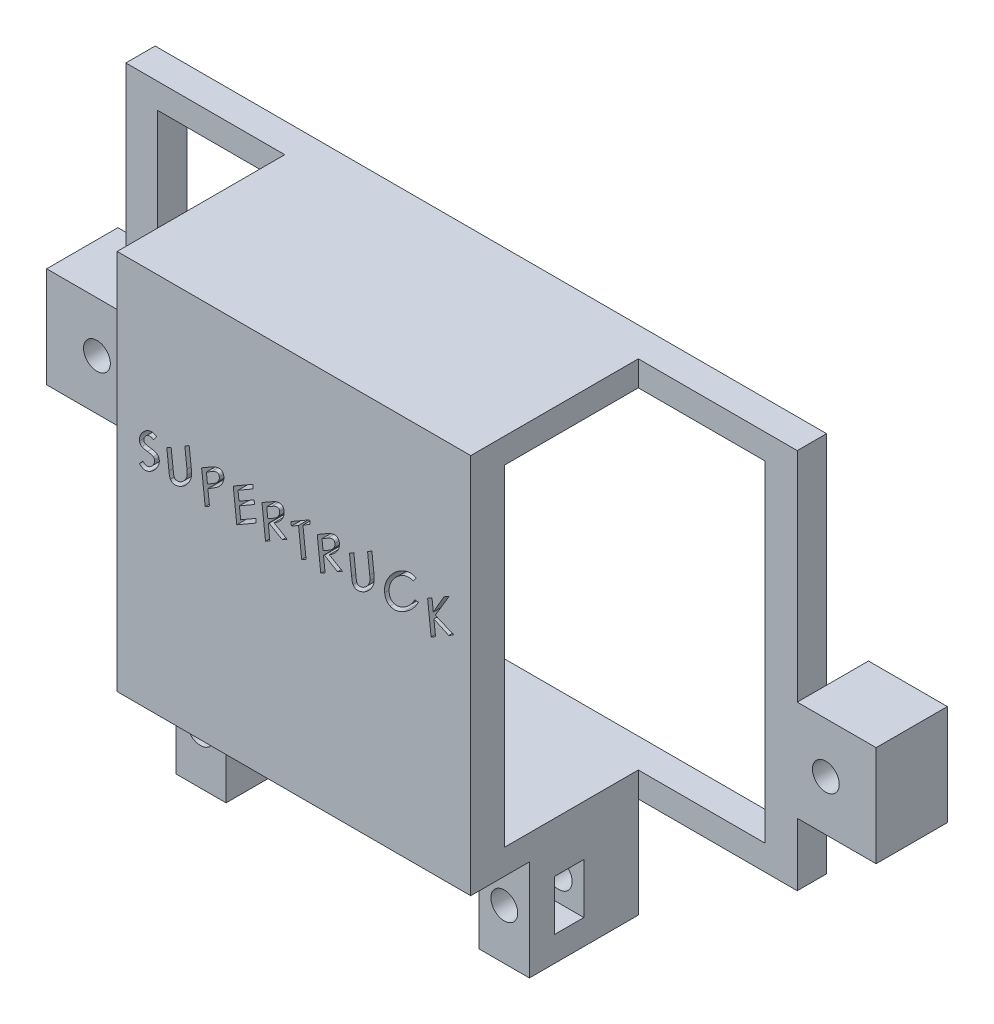
SolidWorks part; units mm, degrees
ref_plane "Plano frontal" through (0, 0, 0) normal (0, 0, 1) x (1, 0, 0)
ref_plane "Plano superior" through (0, 0, 0) normal (0, 1, 0) x (1, 0, 0)
ref_plane "Plano direito" through (0, 0, 0) normal (1, 0, 0) x (0, 0, -1)
sketch "Esboço1" plane through (0, 0, 0) normal (0, 0, 1) x (1, 0, 0)
  line L0 (0, 0) -> (0, 10.5) construction
  line L1 (0, 0) -> (-72.5, 0)
  line L2 (0, 0) -> (0, 39.5)
  line L3 (0, 39.5) -> (-72.5, 39.5)
  line L4 (-72.5, 0) -> (-72.5, 39.5)
  line L5 (-72.5, 0) -> (-72.5, 10.5) construction
  line L6 (0, 10.5) -> (7.25, 10.5) construction
  line L7 (-72.5, 10.5) -> (-79.75, 10.5) construction
  line L8 (-72.5, 39.5) -> (-75.5, 39.5) construction
  line L9 (-72.5, 39.5) -> (-72.5, 42.5) construction
  line L10 (0, 0) -> (3, 0) construction
  line L11 (0, 0) -> (0, -3) construction
  line L12 (-79.75, 10.5) -> (-79.75, 16.5) construction
  line L13 (-76.3022, 42.5) -> (3.836, 42.5)
  line L14 (-76.3022, 42.5) -> (-76.3022, -3)
  line L15 (-76.3022, -3) -> (3.836, -3)
  line L16 (3.836, 42.5) -> (3.836, -3)
  line L17 (-79.75, 10.5) -> (-85.75, 10.5) construction
  line L18 (-79.75, 10.5) -> (-79.75, 4.5) construction
  line L19 (7.25, 10.5) -> (7.25, 16.5) construction
  line L20 (7.25, 10.5) -> (13.25, 10.5) construction
  line L21 (7.25, 10.5) -> (7.25, 4.5) construction
  line L23 (-85.75, 16.5) -> (-76.3022, 16.5)
  line L24 (-85.75, 16.5) -> (-85.75, 4.5)
  line L25 (-85.75, 4.5) -> (-76.3022, 4.5)
  line L26 (-76.3022, 16.5) -> (-76.3022, 4.5)
  line L27 (13.25, 4.5) -> (3.836, 4.5)
  line L28 (13.25, 4.5) -> (13.25, 16.5)
  line L29 (13.25, 16.5) -> (3.836, 16.5)
  line L30 (3.836, 4.5) -> (3.836, 16.5)
  circle A0 centre (-79.75, 10.5) radius 1.6
  circle A1 centre (7.25, 10.5) radius 1.6
extrude "Ressalto-extrusão1" add sketch "Esboço1" along normal blind 5 contours L24 L25 L14 L23 A0 | L28 L29 L16 L27 A1
ref_plane "Plano1" through (0, 0, 5) normal (0, 0, 1) x (1, 0, 0)
sketch "Esboço2" plane through (0, 0, 5) normal (0, 0, 1) x (1, 0, 0)
  line L4 (-72.5, 0) -> (0, 0)
  line L5 (-72.5, 39.5) -> (-72.5, 0)
  line L6 (0, 39.5) -> (-72.5, 39.5)
  line L7 (0, 0) -> (0, 39.5)
  line L8 (-72.5, 0) -> (0, 0)
  line L9 (-72.5, 39.5) -> (-72.5, 0)
  line L10 (0, 39.5) -> (-72.5, 39.5)
  line L11 (0, 0) -> (0, 39.5)
  line L12 (-76.3022, 16.5) -> (-85.75, 16.5)
  line L13 (-76.3022, 4.5) -> (-76.3022, 16.5)
  line L14 (-85.75, 4.5) -> (-76.3022, 4.5)
  line L15 (-85.75, 16.5) -> (-85.75, 4.5)
  line L16 (-76.3022, 16.5) -> (-85.75, 16.5)
  line L17 (-76.3022, 4.5) -> (-76.3022, 16.5)
  line L18 (-85.75, 4.5) -> (-76.3022, 4.5)
  line L19 (-85.75, 16.5) -> (-85.75, 4.5)
  line L20 (3.836, 42.5) -> (-76.3022, 42.5)
  line L21 (-76.3022, 42.5) -> (-76.3022, -3)
  line L22 (-76.3022, -3) -> (3.836, -3)
  line L23 (3.836, -3) -> (3.836, 42.5)
  line L24 (3.836, 42.5) -> (-76.3022, 42.5)
  line L25 (-76.3022, 42.5) -> (-76.3022, -3)
  line L26 (-76.3022, -3) -> (3.836, -3)
  line L27 (3.836, -3) -> (3.836, 42.5)
  line L28 (3.836, 4.5) -> (13.25, 4.5)
  line L29 (13.25, 4.5) -> (13.25, 16.5)
  line L30 (13.25, 16.5) -> (3.836, 16.5)
  line L31 (3.836, 16.5) -> (3.836, 4.5)
  line L32 (3.836, 4.5) -> (13.25, 4.5)
  line L33 (13.25, 4.5) -> (13.25, 16.5)
  line L34 (13.25, 16.5) -> (3.836, 16.5)
  line L35 (3.836, 16.5) -> (3.836, 4.5)
  circle A1 centre (7.25, 10.5) radius 1.6
  circle A2 centre (7.25, 10.5) radius 1.6
  circle A3 centre (-79.75, 10.5) radius 1.6
  circle A4 centre (-79.75, 10.5) radius 1.6
  dimension "D1" = 0
  dimension "D2" = 0
  dimension "D3" = 0
  dimension "D4" = 0
  dimension "D5" = 0
  dimension "D6" = 0
extrude "Ressalto-extrusão2" add sketch "Esboço2" along normal blind 3.5 contours L26 L27 L24 L25 L17 L11 L8 L9 L10 | L16 L19 L18 L17 A4 | L33 L34 L27 L32 A2
sketch "Esboço4" plane through (0, 0, 8.5) normal (0, 0, 1) x (1, 0, 0)
  line L0 (-36.25, 0) -> (-36.25, -21.3357) construction
  line L1 (-72.5, 0) -> (0, 0) construction
  line L2 (-36.2331, -3) -> (-21.1331, -3) construction
  line L3 (-36.2331, -3) -> (-51.3331, -3) construction
  line L4 (-51.3331, -3) -> (-51.3331, -15)
  line L5 (-21.1331, -15) -> (-21.1331, -3)
  line L6 (-21.1331, -15) -> (-15.1331, -15)
  line L7 (-15.1331, -15) -> (-15.1331, 0)
  line L8 (-15.1331, 0) -> (-51.3331, 0)
  line L9 (-51.3331, -15) -> (-57.3331, -15)
  line L10 (-57.3331, -15) -> (-57.3331, 0)
  line L11 (-57.3331, 0) -> (-51.3331, 0)
  line L12 (-76.3022, -3) -> (3.836, -3)
  line L13 (3.836, -3) -> (3.836, 4.5)
  line L14 (3.836, 4.5) -> (13.25, 4.5)
  line L15 (13.25, 4.5) -> (13.25, 16.5)
  line L16 (13.25, 16.5) -> (3.836, 16.5)
  line L17 (3.836, 16.5) -> (3.836, 42.5)
  line L18 (3.836, 42.5) -> (-76.3022, 42.5)
  line L19 (-76.3022, 42.5) -> (-76.3022, 16.5)
  line L20 (-76.3022, 16.5) -> (-85.75, 16.5)
  line L21 (-85.75, 16.5) -> (-85.75, 4.5)
  line L22 (-85.75, 4.5) -> (-76.3022, 4.5)
  line L23 (-76.3022, 4.5) -> (-76.3022, -3)
  line L24 (-76.3022, -3) -> (3.836, -3)
  line L25 (3.836, -3) -> (3.836, 4.5)
  line L26 (3.836, 4.5) -> (13.25, 4.5)
  line L27 (13.25, 4.5) -> (13.25, 16.5)
  line L28 (13.25, 16.5) -> (3.836, 16.5)
  line L29 (3.836, 16.5) -> (3.836, 42.5)
  line L30 (3.836, 42.5) -> (-76.3022, 42.5)
  line L31 (-76.3022, 42.5) -> (-76.3022, 16.5)
  line L32 (-76.3022, 16.5) -> (-85.75, 16.5)
  line L33 (-85.75, 16.5) -> (-85.75, 4.5)
  line L34 (-85.75, 4.5) -> (-76.3022, 4.5)
  line L35 (-76.3022, 4.5) -> (-76.3022, -3)
  line L36 (-21.1331, -3) -> (-51.3331, -3)
  line M16 (0, 0) -> (-72.5, 0)
  line M19 (-76.3022, -3) -> (3.836, -3)
  dimension "D1" = 0
extrude "Ressalto-extrusão4" add sketch "Esboço4" along normal blind 13 contours L10 L7 M19 M16 | L6 L7 L5 M19 | L10 L9 L4 M19
sketch "Esboço5" plane through (0, 0, 8.5) normal (0, 0, 1) x (1, 0, 0)
  line L0 (0, 39.5) -> (-72.5, 39.5) construction
  line L1 (-57.3331, 39.5) -> (-15.1331, 39.5)
  line L2 (-57.3331, 39.5) -> (-57.3331, 42.5)
  line L3 (-57.3331, 42.5) -> (-15.1331, 42.5)
  line L4 (-15.1331, 39.5) -> (-15.1331, 42.5)
  line L5 (3.836, 42.5) -> (-76.3022, 42.5) construction
extrude "Ressalto-extrusão5" add sketch "Esboço5" along normal blind 16
sketch "Esboço6" plane through (0, 0, 24.5) normal (0, 0, 1) x (1, 0, 0)
  line L4 (-57.3331, 42.5) -> (-57.3331, 39.5)
  line L5 (-57.3331, 39.5) -> (-15.1331, 39.5)
  line L6 (-15.1331, 39.5) -> (-15.1331, 42.5)
  line L7 (-15.1331, 42.5) -> (-57.3331, 42.5)
  line L8 (-57.3331, 42.5) -> (-57.3331, 39.5)
  line L9 (-57.3331, 39.5) -> (-15.1331, 39.5)
  line L10 (-15.1331, 39.5) -> (-15.1331, 42.5)
  line L11 (-15.1331, 42.5) -> (-57.3331, 42.5)
  dimension "D1" = 0
extrude "Ressalto-extrusão6" add sketch "Esboço6" along normal blind 4
sketch "Esboço7" plane through (0, 39.5, 0) normal (0, -1, 0) x (1, 0, 0)
  line L0 (-15.1331, 28.5) -> (-15.1331, 8.5) construction
  line L1 (-57.3331, 28.5) -> (-15.1331, 28.5)
  line L2 (-57.3331, 28.5) -> (-57.3331, 24.5)
  line L3 (-57.3331, 24.5) -> (-15.1331, 24.5)
  line L4 (-15.1331, 28.5) -> (-15.1331, 24.5)
sketch "Esboço8" plane through (0, 0, 21.5) normal (0, 0, 1) x (1, 0, 0)
  line L0 (-15.1331, -15) -> (-15.1331, 0) construction
  line L1 (-57.3331, 0) -> (-15.1331, 0)
  line L2 (-57.3331, 0) -> (-57.3331, -3)
  line L3 (-57.3331, -3) -> (-15.1331, -3)
  line L4 (-15.1331, 0) -> (-15.1331, -3)
extrude "Ressalto-extrusão7" add sketch "Esboço8" along normal blind 10
extrude "Ressalto-extrusão8" add sketch "Esboço7" along normal up to next contours L3 L4 L1 L2
sketch "Esboço10" plane through (0, 0, 31.5) normal (0, 0, 1) x (1, 0, 0)
  line L4 (-57.3331, 0) -> (-57.3331, -3)
  line L5 (-57.3331, -3) -> (-15.1331, -3)
  line L6 (-15.1331, -3) -> (-15.1331, 0)
  line L7 (-15.1331, 0) -> (-57.3331, 0)
  line L8 (-57.3331, 0) -> (-57.3331, -3)
  line L9 (-57.3331, -3) -> (-15.1331, -3)
  line L10 (-15.1331, -3) -> (-15.1331, 0)
  line L11 (-15.1331, 0) -> (-57.3331, 0)
  dimension "D1" = 0
extrude "Corte-extrusão1" cut sketch "Esboço10" against normal up to vertex (3 mm away)
sketch "Esboço11" plane through (0, 0, 21.5) normal (0, 0, 1) x (1, 0, 0)
  line L0 (-57.3331, -9) -> (-54.3974, -9) construction
  line L1 (-57.3331, -15) -> (-57.3331, -3) construction
  line L2 (-15.1331, -9) -> (-18.1331, -9) construction
  line L3 (-15.1331, -15) -> (-15.1331, -3) construction
  circle A0 centre (-54.3974, -9) radius 1.6
  circle A1 centre (-18.1331, -9) radius 1.6
extrude "Corte-extrusão4" cut sketch "Esboço11" against normal through all
sketch "Esboço12" plane through (-57.3331, 0, 0) normal (-1, 0, 0) x (0, 0, 1)
  line L0 (21.5, -10.6) -> (21.5, -7.4) construction
  line L1 (21.5, -10.6) -> (21.5, -7.4)
  line L2 (21.5, -7.4) -> (8.5, -7.4) construction
  line L3 (8.5, -15) -> (8.5, -3) construction
  line L4 (21.5, -10.6) -> (8.5, -10.6) construction
  line L5 (15, -9) -> (15, -6)
  line L6 (15, -6) -> (18.5, -6)
  line L7 (18.5, -6) -> (18.5, -12)
  line L8 (18.5, -12) -> (15, -12)
  line L9 (15, -12) -> (15, -9)
extrude "Corte-extrusão5" cut sketch "Esboço12" against normal through all contours L9 L8 L7 L6 L5
sketch "Esboço13" plane through (0, 0, 28.5) normal (0, 0, 1) x (1, 0, 0)
  line L0 (-57.3331, 19.75) -> (-34.1818, 19.75) construction
  line L1 (-57.3331, 42.5) -> (-57.3331, -3) construction
  text T0 "<b><i><r30><r30><r30><r30>SUPERTRUCK</r></r></r></r></i></b>" font "Century Gothic" height 3.5
extrude "Corte-extrusão7" cut sketch "Esboço13" against normal through all
